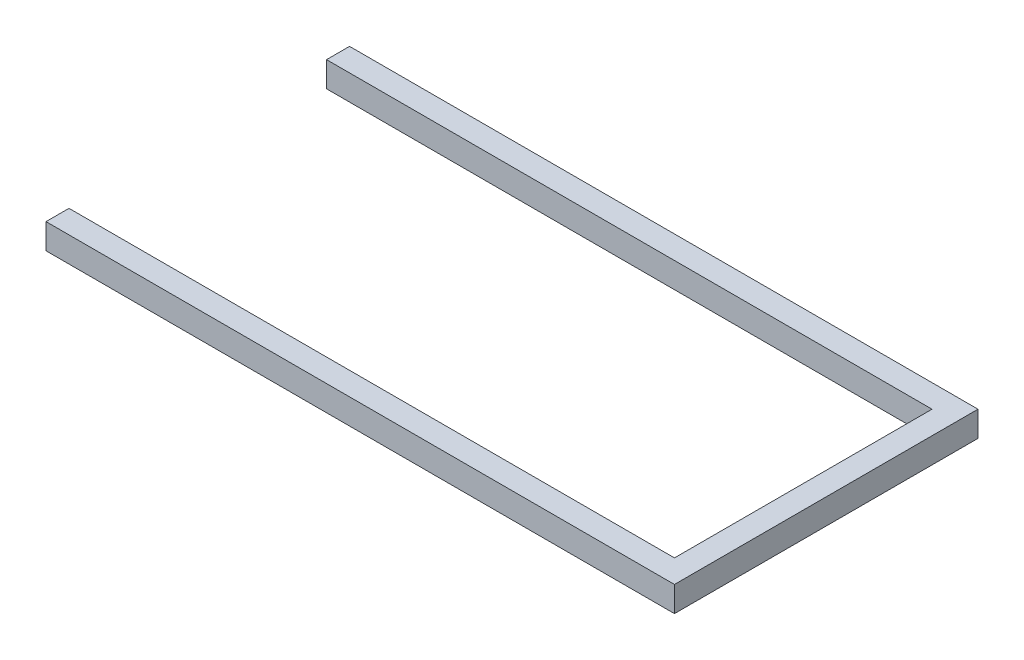
SolidWorks part; units mm, degrees
ref_plane "Front Plane" through (0, 0, 0) normal (0, 0, 1) x (1, 0, 0)
ref_plane "Top Plane" through (0, 0, 0) normal (0, 1, 0) x (1, 0, 0)
ref_plane "Right Plane" through (0, 0, 0) normal (1, 0, 0) x (0, 0, -1)
sketch "Sketch1" plane through (0, 0, 0) normal (0, 1, 0) x (1, 0, 0)
  line L0 (-2.5, -2.5) -> (-2.5, 0)
  line L1 (0, 0) -> (63.325, 0)
  line L3 (0, 28) -> (63.325, 28)
  line L4 (63.325, 0) -> (63.325, 28)
  line L5 (-2.5, 30.5) -> (65.825, 30.5)
  line L6 (65.825, -2.5) -> (65.825, 30.5)
  line L7 (-2.5, -2.5) -> (65.825, -2.5)
  line L8 (0, 28) -> (-2.5, 28)
  line L9 (0, 0) -> (-2.5, 0)
  line L10 (-2.5, 28) -> (-2.5, 30.5)
  line L11 (-2.5, -2.5) -> (-2.5, 30.5) construction
  line L12 (0, 0) -> (0, 28) construction
  dimension "D2" = 33
  dimension "D3" = 68.325
  dimension "D1" = 2.5
extrude "Boss-Extrude1" add sketch "Sketch1" along normal blind 2.75
